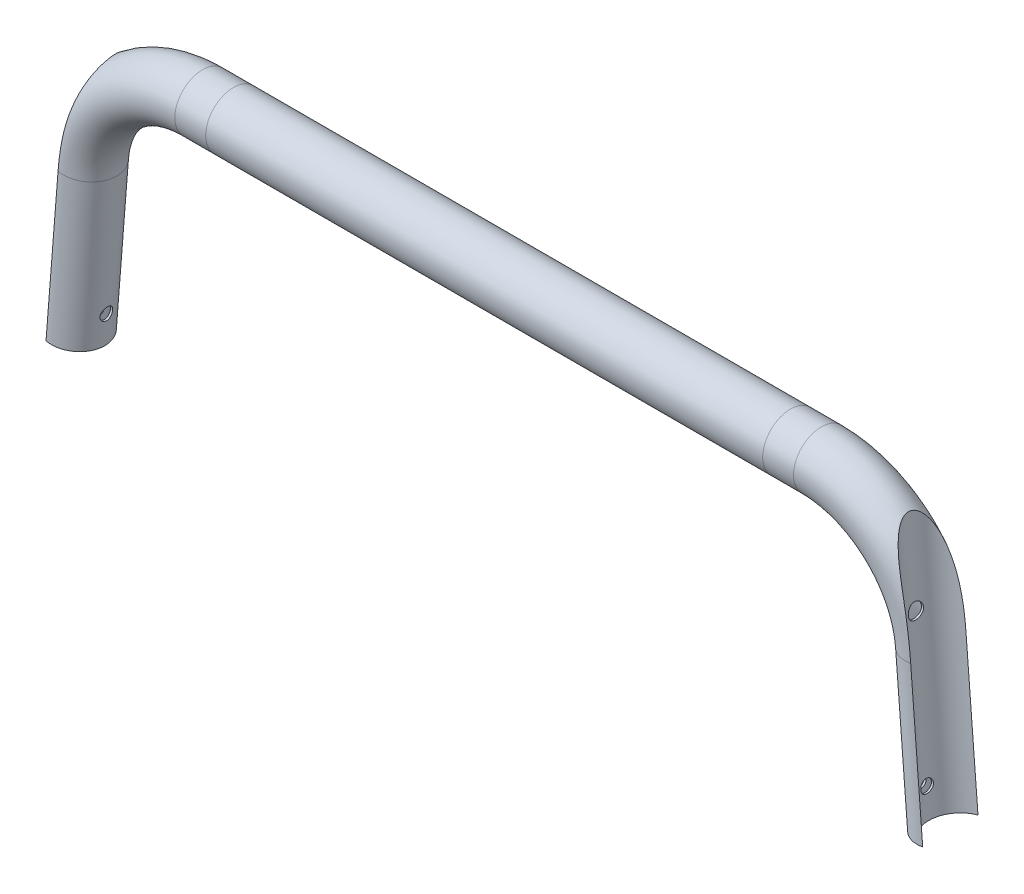
SolidWorks part; units mm, degrees
ref_plane "Front Plane" through (0, 0, 0) normal (0, 0, 1) x (1, 0, 0)
ref_plane "Top Plane" through (0, 0, 0) normal (0, 1, 0) x (1, 0, 0)
ref_plane "Right Plane" through (0, 0, 0) normal (1, 0, 0) x (0, 0, -1)
sketch "Sketch1" plane through (0, 0, 0) normal (0, 0, 1) x (1, 0, 0)
  line L0 (-110, 0) -> (110, 0)
  line L1 (0, 0) -> (0, -80) construction
  line L3 (-171.8, -101.9) -> (-167.044, -41.4693)
  line L4 (-122.1827, 0) -> (-110, 0)
  line L5 (171.8, -101.9) -> (167.044, -41.4693)
  line L6 (122.1827, 0) -> (110, 0)
  arc A0 (167.044, -41.4693) -> (122.1827, 0) centre (122.1827, -45) ccw
  arc A1 (-122.1827, 0) -> (-167.044, -41.4693) centre (-122.1827, -45) ccw
  point P4 (0, 0)
  point P11 (0, -80)
  dimension "D5" = 45
  dimension "D1" = 220
  dimension "D2" = 101.9
  dimension "D3" = 94.5
  dimension "D4" = 94.5
  dimension "D6" = 101.9
  dimension "D7" = 343.6
ref_plane "Plane1" through (-171.8, -101.9, 0) normal (-0.0785, -0.9969, 0) x (-0.9969, 0.0785, 0)
sketch "Sketch2" plane through (-171.8, -101.9, 0) normal (-0.0785, -0.9969, 0) x (-0.9969, 0.0785, 0)
  line L0 (-41.4693, 0) -> (0, 0) construction
  circle A0 centre (0, 0) radius 11
  circle A1 centre (0, 0) radius 10.2
  dimension "D1" = 0.8
sweep "Sweep1" add profiles "Sketch2" path "Sketch1"
sketch "Sketch3" plane through (9.0279, -114.7104, 0) normal (0.0785, -0.9969, 0) x (0.9969, 0.0785, 0)
  line L0 (163.2754, 0) -> (167.2754, 0) construction
  circle A0 centre (167.2754, 0) radius 11.2358
  dimension "D2" = 22.4716
  dimension "D1" = 4
extrude "Cut-Extrude1" cut sketch "Sketch3" against normal through all
mirror "Mirror1" about plane through (0, 0, 0) normal (1, 0, 0) of "Cut-Extrude1"
sketch "Sketch6" plane through (9.0279, -114.7104, 0) normal (0.0785, -0.9969, 0) x (0.9969, 0.0785, 0)
  line L0 (163.2754, 0) -> (167.2754, 0) construction
  arc A0 (163.2185, 10.4778) -> (163.2185, -10.4778) centre (167.2754, 0) ccw
  arc A2 (160.8913, 10.2032) -> (160.8913, -10.2032) centre (167.2754, 0) ccw
  arc A3 (160.8913, -10.2032) -> (163.2185, -10.4778) centre (163.2754, 0) ccw
  circle A4 centre (167.2754, 0) radius 12.0358 construction
  circle A5 centre (167.2754, 0) radius 11.2358 construction
  arc A6 (163.2185, 10.4778) -> (160.8913, 10.2032) centre (163.2754, 0) ccw
  dimension "D1" = 0.8
extrude "Boss-Extrude1" add sketch "Sketch6" against normal up to next
mirror "Mirror2" about plane through (0, 0, 0) normal (1, 0, 0) of "Boss-Extrude1"
sketch "Sketch7" plane through (9.0279, -114.7104, 0) normal (0.0785, -0.9969, 0) x (0.9969, 0.0785, 0)
  line L0 (152.2754, 0) -> (163.2754, 0)
  arc A0 (164.62, 10.9175) -> (164.62, -10.9175) centre (163.2754, 0) ccw construction
ref_plane "Plane2" through (171.8, -101.9, 0) normal (0.9969, 0.0785, 0) x (0, 0, -1)
sketch "Sketch8" plane through (171.8, -101.9, 0) normal (0.9969, 0.0785, 0) x (0, 0, -1)
  line L0 (0, 0.0022) -> (0, 11.4022) construction
  circle A0 centre (0, 11.4022) radius 2.5
  dimension "D1" = 11.4
extrude "Cut-Extrude2" cut sketch "Sketch8" against normal up to surface (333.4716 mm away)
mirror "Mirror3" about plane through (0, 0, 0) normal (1, 0, 0) of "Cut-Extrude2"
ref_plane "Plane3" through (180, 0, 0) normal (1, 0, 0) x (0, 0, -1)
sketch "Sketch9" plane through (180, 0, 0) normal (1, 0, 0) x (0, 0, -1)
  circle A0 centre (0, -33.4448) radius 3
extrude "Cut-Extrude3" cut sketch "Sketch9" against normal up to next
